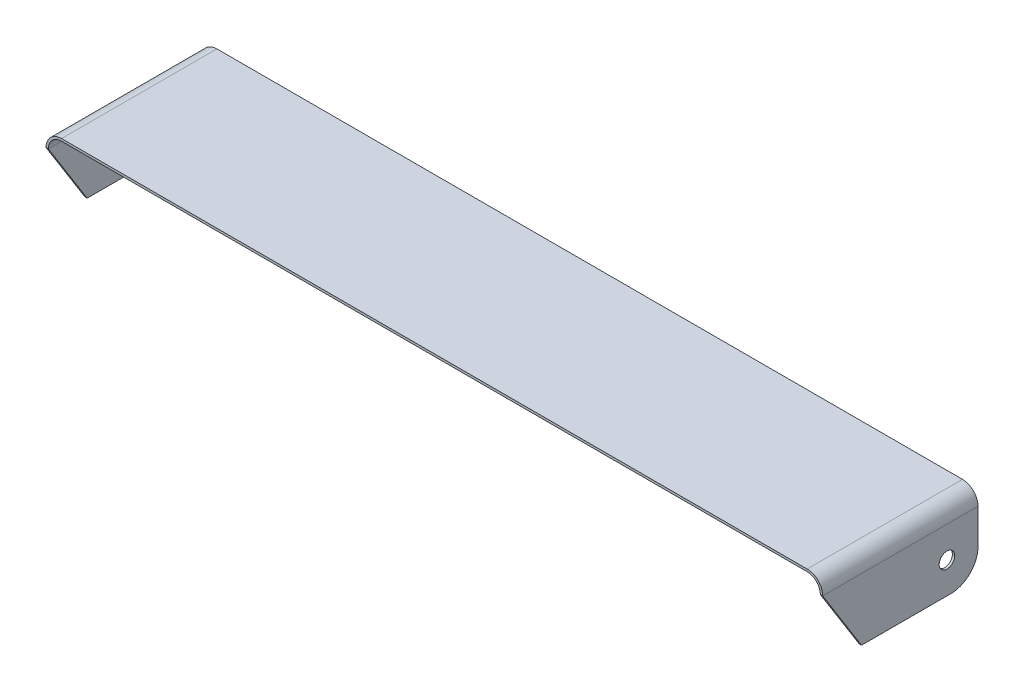
SolidWorks part; units mm, degrees
ref_plane "Front Plane" through (0, 0, 0) normal (0, 0, 1) x (1, 0, 0)
ref_plane "Top Plane" through (0, 0, 0) normal (0, 1, 0) x (1, 0, 0)
ref_plane "Right Plane" through (0, 0, 0) normal (1, 0, 0) x (0, 0, -1)
sketch "Sketch1" plane through (0, 0, 0) normal (0, 0, 1) x (1, 0, 0)
  line L0 (-500, 171.9733) -> (-500, 251.9733)
  line L1 (-480, 271.9733) -> (480, 271.9733)
  line L2 (500, 251.9733) -> (500, 171.9733)
  line L3 (-497, 171.9733) -> (-497, 251.9733)
  line L4 (-480, 268.9733) -> (480, 268.9733)
  line L5 (497, 251.9733) -> (497, 171.9733)
  line L6 (-497, 171.9733) -> (-500, 171.9733)
  line L7 (500, 171.9733) -> (497, 171.9733)
  arc A0 (480, 271.9733) -> (500, 251.9733) centre (480, 251.9733) cw
  arc A1 (-500, 251.9733) -> (-480, 271.9733) centre (-480, 251.9733) cw
  arc A2 (-497, 251.9733) -> (-480, 268.9733) centre (-480, 251.9733) cw
  arc A3 (480, 268.9733) -> (497, 251.9733) centre (480, 251.9733) cw
  point P11 (500, 271.9733)
  point P14 (-500, 271.9733)
  dimension "D4" = 20
  dimension "D1" = 1000
  dimension "D2" = 100
  dimension "D3" = 500
  dimension "D5" = 3
extrude "Boss-Extrude1" add sketch "Sketch1" along normal mid plane 200
sketch "Sketch2" plane through (500, 0, 0) normal (1, 0, 0) x (0, 0, -1)
  line L0 (-100, 171.9733) -> (-50, 171.9733)
  line L1 (-100, 171.9733) -> (100, 171.9733) construction
  line L2 (-50, 171.9733) -> (-100, 251.9733)
  line L3 (-100, 171.9733) -> (-100, 251.9733) construction
  line L4 (-100, 251.9733) -> (-100, 171.9733)
  dimension "D1" = 80
  dimension "D2" = 50
extrude "Cut-Extrude1" cut sketch "Sketch2" against normal through all
sketch "Sketch3" plane through (500, 0, 0) normal (1, 0, 0) x (0, 0, -1)
  line L0 (-100, 271.9733) -> (100, 271.9733) construction
  line L1 (100, 171.9733) -> (100, 251.9733) construction
  circle A0 centre (60, 211.9733) radius 10
  dimension "D3" = 20
  dimension "D1" = 60
  dimension "D2" = 40
extrude "Cut-Extrude2" cut sketch "Sketch3" against normal through all
fillet "Fillet1" radius 35 2 edges at (-498.5, 171.9733, -100) (498.5, 171.9733, -100)
